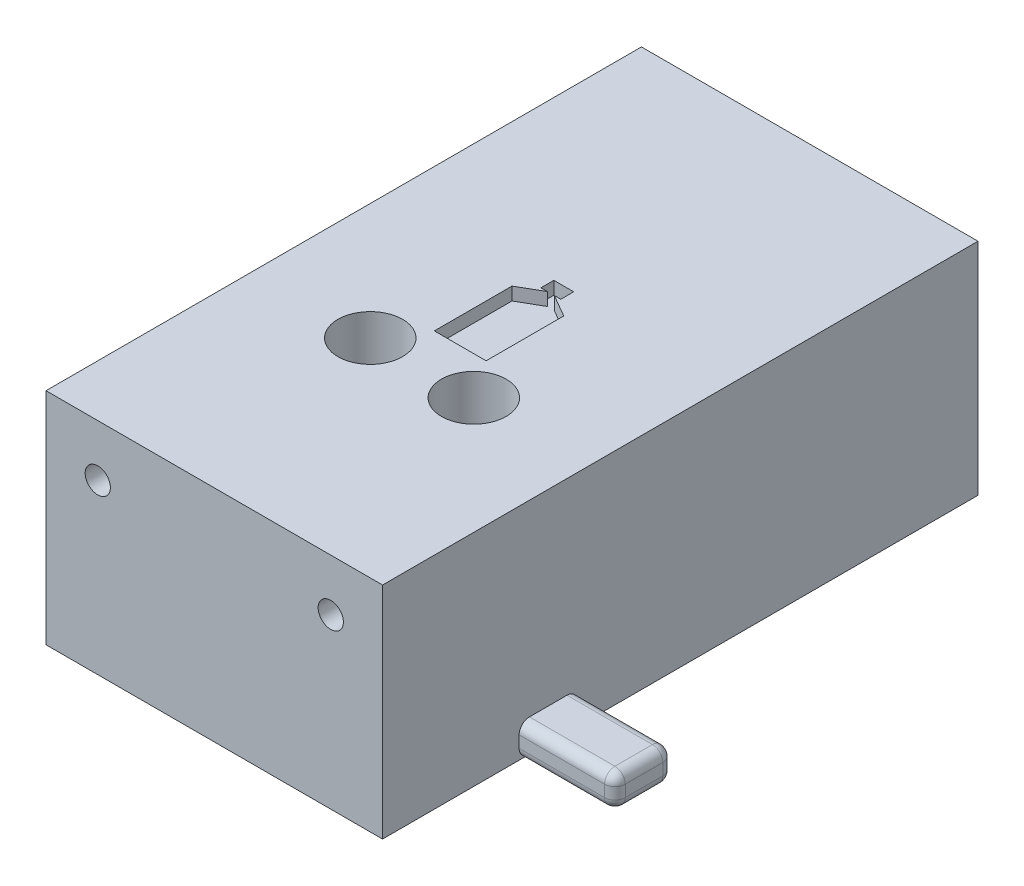
SolidWorks part; units mm, degrees
material "ABS"
ref_plane "正面" through (0, 0, 0) normal (0, 0, 1) x (1, 0, 0)
ref_plane "平面" through (0, 0, 0) normal (0, 1, 0) x (1, 0, 0)
ref_plane "右側面" through (0, 0, 0) normal (1, 0, 0) x (0, 0, -1)
sketch "ｽｹｯﾁ1" plane through (0, 0, 0) normal (0, 0, 1) x (1, 0, 0)
  line L1 (13, -8.5) -> (-13, -8.5)
  line L2 (13, -8.5) -> (13, 8.5)
  line L3 (13, 8.5) -> (-13, 8.5)
  line L4 (-13, -8.5) -> (-13, 8.5)
  line L5 (13, -8.5) -> (-13, 8.5) construction
  line L6 (13, 8.5) -> (-13, -8.5) construction
  point P0 (0, 0)
  dimension "D1" = 26
  dimension "D2" = 17
extrude "ﾎﾞｽ - 押し出し1" add sketch "ｽｹｯﾁ1" against normal blind 46
sketch "ｽｹｯﾁ2" plane through (13, 0, 0) normal (1, 0, 0) x (0, 0, -1)
  line L0 (46, -8.5) -> (0, -8.5) construction
  line L1 (15.05, -6) -> (10.55, -6)
  line L2 (15.05, -6) -> (15.05, -8.5)
  line L3 (15.05, -8.5) -> (10.55, -8.5)
  line L4 (10.55, -6) -> (10.55, -8.5)
  line L5 (15.05, -6) -> (10.55, -8.5) construction
  line L6 (15.05, -8.5) -> (10.55, -6) construction
  line L8 (0, -8.5) -> (0, 8.5) construction
  point P0 (12.8, -7.25)
  dimension "D1" = 12.8
  dimension "D2" = 4.5
  dimension "D3" = 2.5
extrude "ﾎﾞｽ - 押し出し2" add sketch "ｽｹｯﾁ2" along normal blind 7.4
sketch "ｽｹｯﾁ4" plane through (-13, 0, 0) normal (-1, 0, 0) x (0, 0, 1)
  line L0 (-46, -8.5) -> (0, -8.5) construction
  line L1 (-15.3, -5.5) -> (-10.3, -5.5)
  line L2 (-15.3, -5.5) -> (-15.3, -8.5)
  line L3 (-15.3, -8.5) -> (-10.3, -8.5)
  line L4 (-10.3, -5.5) -> (-10.3, -8.5)
  line L5 (-15.3, -5.5) -> (-10.3, -8.5) construction
  line L6 (-15.3, -8.5) -> (-10.3, -5.5) construction
  line L7 (0, 8.5) -> (0, -8.5) construction
  point P0 (-12.8, -7)
  dimension "D1" = 3
  dimension "D2" = 5
  dimension "D3" = 10.3
extrude "ﾎﾞｽ - 押し出し3" add sketch "ｽｹｯﾁ4" along normal blind 7.4
sketch "ｽｹｯﾁ5" plane through (0, 8.5, 0) normal (0, 1, 0) x (1, 0, 0)
  line L0 (13, 16.05) -> (-13, 16.05) construction
  line L1 (13, 46) -> (13, 0) construction
  line L2 (-13, 46) -> (-13, 0) construction
  line L3 (13, 0) -> (-13, 0) construction
  circle A0 centre (4, 16.05) radius 1.2
  circle A1 centre (-4, 16.05) radius 1.2
  point P12 (0, 0)
  dimension "D2" = 8
  dimension "D3" = 4
  dimension "D4" = 2.4
  dimension "D1" = 16.05
extrude "ｶｯﾄ - 押し出し1" cut sketch "ｽｹｯﾁ5" against normal through all
sketch "ｽｹｯﾁ6" plane through (0, 8.5, 0) normal (0, 1, 0) x (1, 0, 0)
  line L0 (0, 46) -> (0, 0) construction
  line L1 (13, 46) -> (-13, 46) construction
  line L2 (13, 0) -> (-13, 0) construction
  line L3 (-13, 23) -> (13, 23) construction
  line L4 (-13, 46) -> (-13, 0) construction
  line L5 (13, 46) -> (13, 0) construction
  line L6 (-2, 19) -> (2, 19)
  line L7 (2, 19) -> (2, 25)
  line L8 (2, 25) -> (0.2679, 26)
  line L9 (0.2679, 26) -> (0.7679, 26)
  line L10 (0.7679, 26) -> (0.7679, 27)
  line L11 (0.7679, 27) -> (-0.7679, 27)
  line L12 (-2, 19) -> (-2, 25)
  line L13 (-2, 25) -> (-0.2679, 26)
  line L14 (-0.2679, 26) -> (-0.7679, 26)
  line L15 (-0.7679, 26) -> (-0.7679, 27)
  point P20 (0, 19)
  point P24 (0, 27)
  dimension "D1" = 2
  dimension "D2" = 6
  dimension "D3" = 0.5
  dimension "D4" = 1
  dimension "D5" = 120
  dimension "D6" = 1
  dimension "D7" = 4
extrude "ｶｯﾄ - 押し出し2" cut sketch "ｽｹｯﾁ6" against normal blind 1
sketch "ｽｹｯﾁ8" plane through (0, 8.5, 0) normal (0, 1, 0) x (1, 0, 0)
  circle A0 centre (-4, 16.05) radius 2.5
  circle A1 centre (4, 16.05) radius 2.5
  dimension "D1" = 5
  dimension "D2" = 5
extrude "ｶｯﾄ - 押し出し3" cut sketch "ｽｹｯﾁ8" against normal blind 4
sketch "ｽｹｯﾁ9" plane through (0, 0, 0) normal (0, 0, 1) x (1, 0, 0)
  line L0 (-13, 4.5) -> (13, 4.5) construction
  line L1 (-13, 8.5) -> (-13, -8.5) construction
  line L2 (13, -8.5) -> (13, 8.5) construction
  line L3 (13, 8.5) -> (-13, 8.5) construction
  line L4 (0, 8.5) -> (0, -8.5) construction
  line L5 (-13, -8.5) -> (13, -8.5) construction
  circle A0 centre (-9, 4.5) radius 0.975
  circle A1 centre (9, 4.5) radius 0.975
  dimension "D2" = 1.95
  dimension "D3" = 4
  dimension "D1" = 4
extrude "ｶｯﾄ - 押し出し4" cut sketch "ｽｹｯﾁ9" against normal blind 5
fillet "ﾌｨﾚｯﾄ1" radius 0.8 16 edges at (-20.4, -7, -15.3) (-20.4, -7, -10.3) (20.4, -7.25, -15.05) (20.4, -7.25, -10.55) (-16.7, -5.5, -10.3) (-16.7, -8.5, -10.3) (-16.7, -8.5, -15.3) (-16.7, -5.5, -15.3) (-20.4, -5.5, -12.8) (-20.4, -8.5, -12.8) (20.4, -8.5, -12.8) (16.7, -8.5, -15.05) (16.7, -8.5, -10.55) (16.7, -6, -15.05) (20.4, -6, -12.8) (16.7, -6, -10.55)
